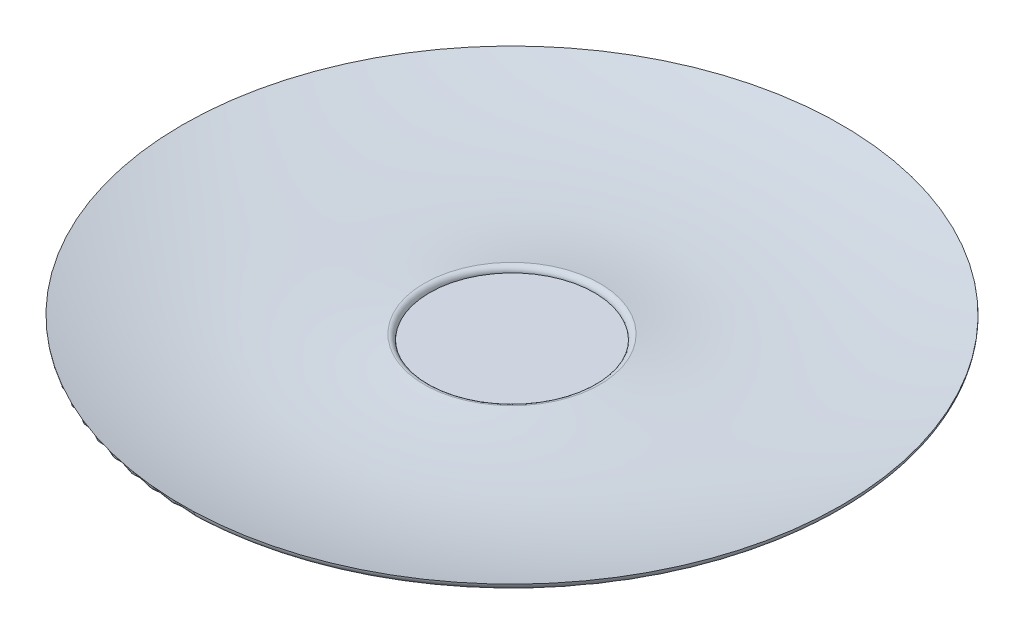
SolidWorks part; units mm, degrees
ref_plane "Front Plane" through (0, 0, 0) normal (0, 0, 1) x (1, 0, 0)
ref_plane "Top Plane" through (0, 0, 0) normal (0, 1, 0) x (1, 0, 0)
ref_plane "Right Plane" through (0, 0, 0) normal (1, 0, 0) x (0, 0, -1)
sketch "Sketch2" plane through (0, 0, 0) normal (0, 0, 1) x (1, 0, 0)
  line L0 (0, 0) -> (20, 0)
  line L1 (0, 0) -> (0, -9.7167)
  line L4 (78.7713, 3.7152) -> (66.216, -0.9345)
  line L5 (0, -9.7167) -> (16, -9.7167)
  arc A0 (20, 0) -> (21.3072, 1.3072) centre (21.3072, 0) cw
  arc A2 (80, 5.2833) -> (78.7713, 3.7152) centre (78.3259, 5.3297) cw
  spline S0 degree 2 poles (21.3072, 1.3072) (50.5893, -3.6487) (80, 5.2833) knots 0 0 0 1 1 1
  spline S1 degree 3 poles (16, -9.7167) (31.9734, -2.8025) (50.0812, -7.4971) (66.216, -0.9345) knots 0 0 0 0 1 1 1 1
  dimension "D1" = 20
  dimension "D2" = 80
  dimension "D3" = 15
  dimension "D4" = 16
revolve "Revolve2" add sketch "Sketch2" angle 360 about L1
